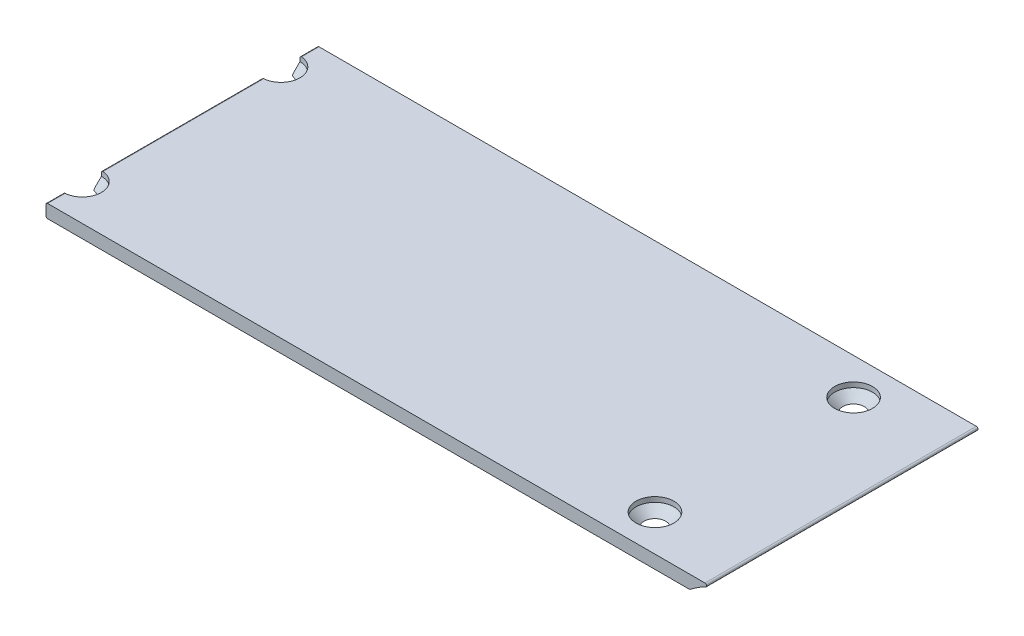
SolidWorks part; units mm, degrees
ref_plane "Ebene vorne" through (0, 0, 0) normal (0, 0, 1) x (1, 0, 0)
ref_plane "Ebene oben" through (0, 0, 0) normal (0, 1, 0) x (1, 0, 0)
ref_plane "Ebene rechts" through (0, 0, 0) normal (1, 0, 0) x (0, 0, -1)
sketch "Skizze1" plane through (0, 0, 0) normal (0, 0, 1) x (1, 0, 0)
  line L0 (0, 23) -> (435, 23) construction
  line L1 (225, 19) -> (417.9926, 19) construction
  line L2 (419.5323, 19) -> (417.9926, 19) construction
  line L3 (225, 23) -> (426.559, 23)
  line L5 (225, 19) -> (417.9926, 19)
  line L12 (225, 25) -> (225, 19) construction
  line L14 (225, 23) -> (225, 19)
  line L16 (419.5323, 19) -> (417.9926, 19)
  arc A2 (426.559, 23) -> (419.5323, 19) centre (435, 0) ccw construction
  arc A3 (426.559, 23) -> (419.5323, 19) centre (435, 0) ccw
extrude "Aufsatz-Linear austragen1" add sketch "Skizze1" against normal up to vertex (49.5 mm away) from vertex at -8.5
fillet "Verrundung1" radius 0.5 4 edges at (225, 19, -29) (225, 23, -29) (426.559, 23, -29) (419.5323, 19, -29)
ref_plane "Ebene1" through (398, 0, 0) normal (1, 0, 0) x (0, 0, -1)
sketch "Skizze2" plane through (225, 0, 0) normal (1, 0, 0) x (0, 0, -1)
  point P0 (19.5, 25)
sketch "Skizze3" plane through (398, 0, 0) normal (1, 0, 0) x (0, 0, -1)
  point P0 (19.5, 25)
sketch "Skizze4" plane through (0, 23, 0) normal (0, 1, 0) x (1, 0, 0)
  point P0 (398, 19.5)
  point P2 (225, 19.5)
hole_wizard "Formsenkung für M5 Senkschraube mit Innensechskant1" positions "Skizze4" profile "Skizze5" countersink size "M5" standard "DIN"
sketch "Skizze5" plane through (398, 23, -19.5) normal (1, 0, 0) x (0, 0, 1)
  line L0 (0, 0) -> (0, 5.6524)
  line L1 (0, 5.6524) -> (2.75, 4)
  line L2 (2.75, 4) -> (2.75, 4.485)
  line L3 (2.75, 4.485) -> (5.735, 1.5)
  line L4 (5.735, 1.5) -> (5.735, 0)
  line L6 (5.735, 0) -> (0, 0)
  line L7 (-2.75, 4.485) -> (-5.735, 1.5) construction
  line L10 (0, 5.6524) -> (-2.75, 4) construction
  line L11 (0, -6.35) -> (0, 107.95) construction
  dimension "Bohrerdurchmesser" = 5.5
  dimension "Bohrungstiefe" = 4
  dimension "Senkdurchmesser2" = 11.47
  dimension "Senkwinkel2" = 90
  dimension "Spitzenwinkel" = 118
  dimension "Kopfspielraum" = 1.5
mirror "Spiegeln1" about plane through (435, 0, -49.5) normal (0, 0, 1) of bodies 104 102
